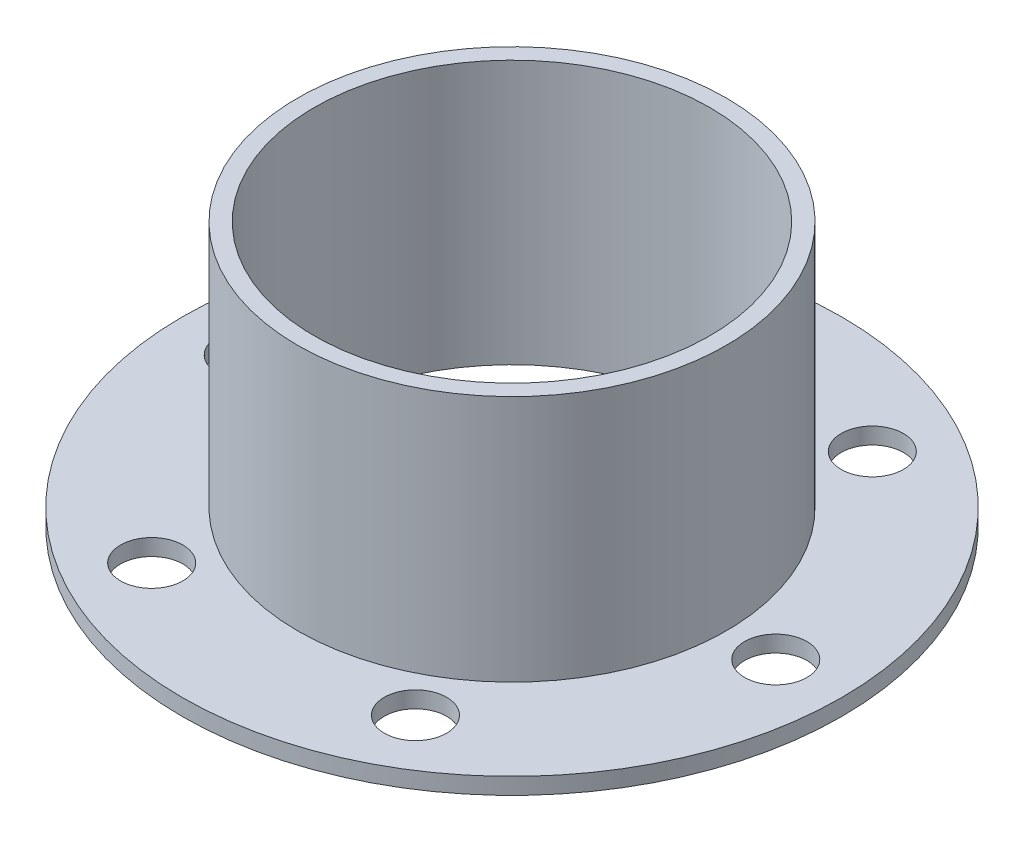
SolidWorks part; units mm, degrees
ref_plane "Front Plane" through (0, 0, 0) normal (0, 0, 1) x (1, 0, 0)
ref_plane "Top Plane" through (0, 0, 0) normal (0, 1, 0) x (1, 0, 0)
ref_plane "Right Plane" through (0, 0, 0) normal (1, 0, 0) x (0, 0, -1)
sketch "Sketch1" plane through (0, 0, 0) normal (0, 0, 1) x (1, 0, 0)
  line L0 (-63.5, 0) -> (-63.5, 3.175)
  line L1 (55, 0) -> (-55, 0) construction
  line L2 (-63.5, 3.175) -> (-41.275, 3.175)
  line L3 (-41.275, 3.175) -> (-41.275, 50.8)
  line L4 (-41.275, 50.8) -> (-38.1, 50.8)
  line L5 (-38.1, 50.8) -> (-38.1, 0)
  line L6 (-38.1, 0) -> (-63.5, 0)
  line L7 (0, -55) -> (0, 55) construction
  line L8 (0, 0) -> (0, 56.6996) construction
  dimension "D1" = 38.1
  dimension "D2" = 3.175
  dimension "D3" = 3.175
  dimension "D4" = 50.8
  dimension "D5" = 25.4
revolve "Revolve1" add sketch "Sketch1" angle 360 about L8
sketch "Sketch3" plane through (0, 3.175, 0) normal (0, 1, 0) x (1, 0, 0)
  line L0 (0, 0) -> (-50.8, 0)
  line L1 (-55, 0) -> (55, 0) construction
  circle A0 centre (-50.8, 0) radius 6
  circle A1 centre (0, 0) radius 63.5 construction
  circle A2 centre (0, 0) radius 63.5
  dimension "D1" = 12
  dimension "D2" = 12.7
extrude "Cut-Extrude1" cut sketch "Sketch3" against normal through all both and the other way through all
pattern_circular "CirPattern1" count 6 over 360 about axis through (0, 0, 0) along (0, 1, 0) of "Cut-Extrude1"
